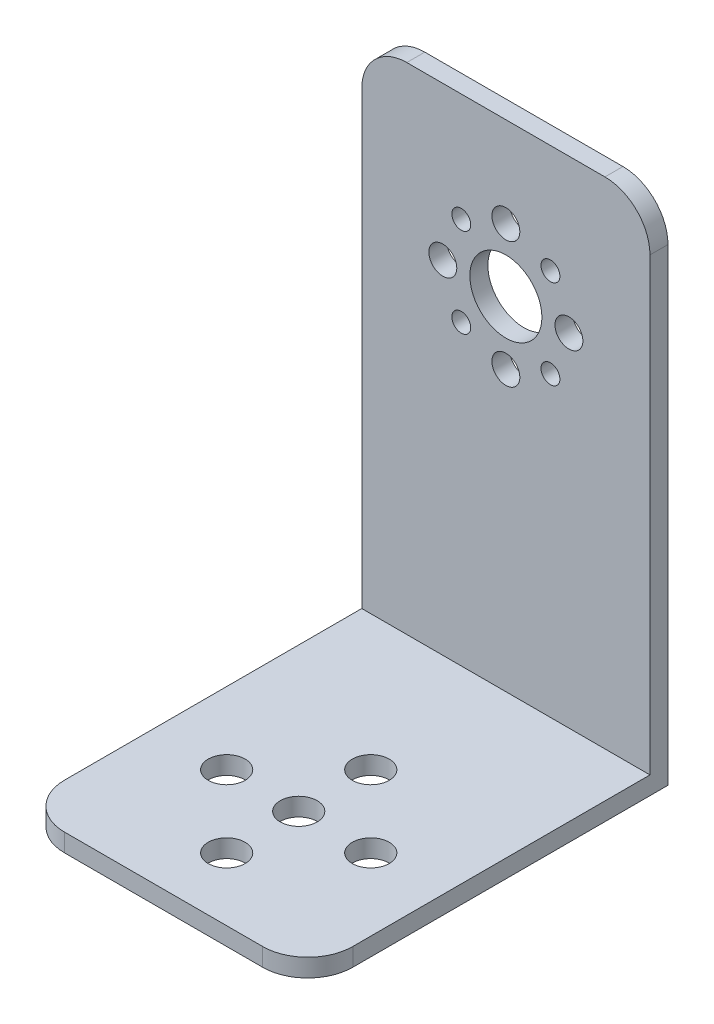
SolidWorks part; units mm, degrees
material "AISI 304"
ref_plane "前视基准面" through (0, 0, 0) normal (0, 0, 1) x (1, 0, 0)
ref_plane "上视基准面" through (0, 0, 0) normal (0, 1, 0) x (1, 0, 0)
ref_plane "右视基准面" through (0, 0, 0) normal (1, 0, 0) x (0, 0, -1)
sketch "草图2" plane through (0, 0, 0) normal (0, 1, 0) x (1, 0, 0)
  line L1 (-16, 20) -> (16, 20)
  line L2 (-16, 20) -> (-16, -20)
  line L3 (-16, -20) -> (16, -20)
  line L4 (16, 20) -> (16, -20)
  line L5 (-16, 20) -> (16, -20) construction
  line L6 (-16, -20) -> (16, 20) construction
  point P0 (0, 0)
  dimension "D1" = 32
  dimension "D2" = 40
extrude "凸台-拉伸1" add sketch "草图2" along normal blind 2
sketch "草图3" plane through (0, 2, 0) normal (0, 1, 0) x (1, 0, 0)
  line L0 (-16, 18) -> (16, 18)
  line L1 (-16, 20) -> (-16, -20) construction
  line L2 (16, -20) -> (16, 20) construction
  line L3 (16, 18) -> (16, 20)
  line L4 (16, 20) -> (-16, 20)
  line L5 (-16, 20) -> (-16, 18)
  dimension "D1" = 2
extrude "凸台-拉伸2" add sketch "草图3" along normal blind 55
sketch "草图6" plane through (0, 2, 0) normal (0, 1, 0) x (1, 0, 0)
  line L0 (-16, -5) -> (36.5581, -5) construction
  line L1 (-16, 18) -> (-16, -20) construction
  line L2 (16, 20) -> (-16, 20) construction
  line L3 (0, 0) -> (0, -31.2484) construction
  circle A0 centre (0, -5) radius 2.05
  circle A1 centre (-8, -5) radius 2.05
  circle A2 centre (8, -5) radius 2.05
  circle A3 centre (0, 3) radius 2.05
  circle A4 centre (0, -13) radius 2.05
  dimension "D2" = 4.1
  dimension "D3" = 4.1
  dimension "D4" = 4.1
  dimension "D5" = 8
  dimension "D6" = 8
  dimension "D7" = 4.1
  dimension "D8" = 4.1
  dimension "D9" = 8
  dimension "D10" = 8
  dimension "D1" = 25
extrude "切除-拉伸2" cut sketch "草图6" against normal through all
fillet "圆角1" radius 5 4 edges at (16, 57, -19) (-16, 57, -19) (-16, 1, 20) (16, 1, 20)
sketch "Sketch1" plane through (0, 0, -18) normal (0, 0, 1) x (1, 0, 0)
  line L0 (0, 0) -> (0, 57) construction
  line L1 (-11, 57) -> (11, 57) construction
  line L2 (0, 40) -> (9.1728, 49.1728) construction
  line L3 (0, 40) -> (11.9998, 40) construction
  circle A0 centre (0, 40) radius 4
  circle A1 centre (0, 40) radius 7 construction
  circle A2 centre (0, 47) radius 1.55
  circle A4 centre (4.9497, 44.9497) radius 1.05
  circle A5 centre (7, 40) radius 1.55
  circle A6 centre (4.9497, 35.0503) radius 1.05
  circle A7 centre (0, 33) radius 1.55
  circle A8 centre (-4.9497, 35.0503) radius 1.05
  circle A9 centre (-4.9497, 44.9497) radius 1.05
  circle A10 centre (-7, 40) radius 1.55
  point P11 (4.9497, 44.9497)
  point P27 (-4.9497, 44.9497)
  dimension "D2" = 8
  dimension "D3" = 14
  dimension "D5" = 2.1
  dimension "D6" = 3.1
  dimension "D1" = 40
  dimension "D4" = 45
extrude "Cut-Extrude1" cut sketch "Sketch1" against normal blind 10
